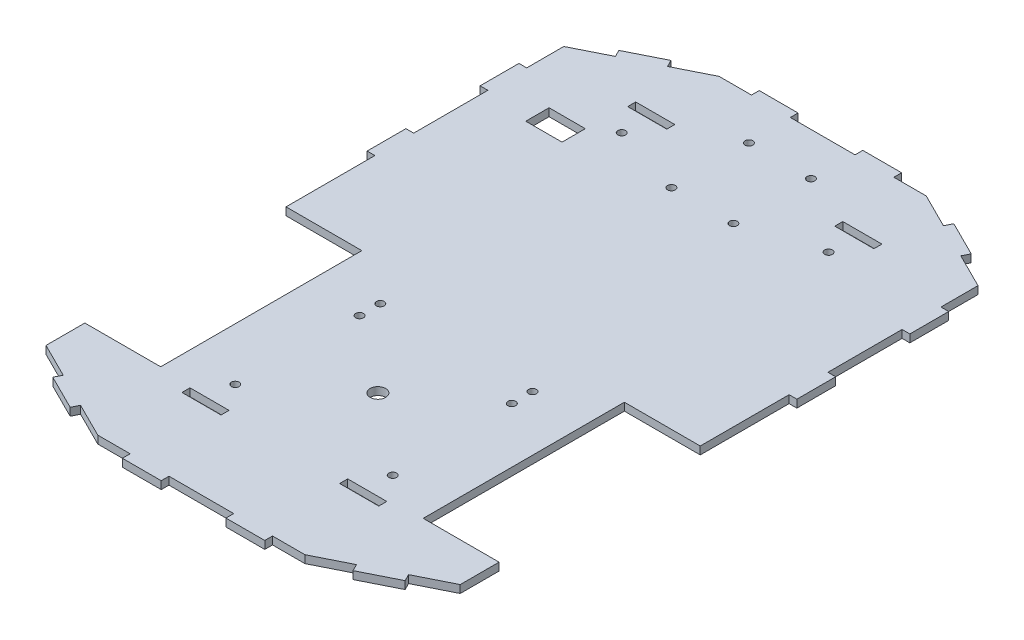
SolidWorks part; units mm, degrees
ref_plane "Front Plane" through (0, 0, 0) normal (0, 0, 1) x (1, 0, 0)
ref_plane "Top Plane" through (0, 0, 0) normal (0, 1, 0) x (1, 0, 0)
ref_plane "Right Plane" through (0, 0, 0) normal (1, 0, 0) x (0, 0, -1)
sketch "Sketch1" plane through (0, 0, 0) normal (0, 1, 0) x (1, 0, 0)
  line L0 (120, 0) -> (133.2918, 6.6459)
  line L1 (40, 0) -> (52.5, 0)
  line L2 (0, 20) -> (0, 35)
  line L3 (40, 240) -> (52.5, 240)
  line L4 (160, 20) -> (160, 35)
  line L5 (120, 240) -> (133.2918, 233.3541)
  line L6 (0, 20) -> (13.2918, 13.3541)
  line L7 (0, 220) -> (13.2918, 226.6459)
  line L8 (0, 35) -> (29.3, 35)
  line L9 (29.3, 35) -> (29.3, 112.71)
  line L10 (29.3, 112.71) -> (0, 112.71)
  line L11 (80, 240) -> (80, 0) construction
  line L12 (0, 112.71) -> (0, 147.0325)
  line L13 (160, 35) -> (130.7, 35)
  line L14 (130.7, 35) -> (130.7, 112.71)
  line L15 (130.7, 112.71) -> (160, 112.71)
  line L16 (160, 112.71) -> (160, 147.0325)
  line L17 (80, 213.7859) -> (0, 213.7859) construction
  line L18 (116.8791, 0) -> (116.8791, 25) construction
  line L19 (32.45, 212.2359) -> (47.55, 212.2359)
  line L20 (32.45, 212.2359) -> (32.45, 215.3359)
  line L21 (32.45, 215.3359) -> (47.55, 215.3359)
  line L22 (47.55, 212.2359) -> (47.55, 215.3359)
  line L23 (32.45, 212.2359) -> (47.55, 215.3359) construction
  line L24 (32.45, 215.3359) -> (47.55, 212.2359) construction
  line L25 (116.8791, 25) -> (97.8791, 25) construction
  line L26 (97.8791, 25) -> (97.8791, 0) construction
  line L27 (160, 32.0731) -> (0, 32.0731) construction
  line L28 (20, 230) -> (14.7857, 240.4286) construction
  line L29 (41.9927, 30.5231) -> (57.0927, 30.5231)
  line L30 (41.9927, 30.5231) -> (41.9927, 33.6231)
  line L31 (41.9927, 33.6231) -> (57.0927, 33.6231)
  line L32 (57.0927, 30.5231) -> (57.0927, 33.6231)
  line L33 (41.9927, 30.5231) -> (57.0927, 33.6231) construction
  line L34 (41.9927, 33.6231) -> (57.0927, 30.5231) construction
  line L35 (11.9502, 229.3292) -> (25.3666, 236.0374)
  line L36 (11.9502, 229.3292) -> (13.2918, 226.6459)
  line L37 (25.3666, 236.0374) -> (26.7082, 233.3541)
  line L38 (20, 10) -> (15, 0) construction
  line L39 (11.9502, 10.6708) -> (25.3666, 3.9626)
  line L40 (11.9502, 10.6708) -> (13.2918, 13.3541)
  line L41 (25.3666, 3.9626) -> (26.7082, 6.6459)
  line L42 (0, 176.355) -> (0, 190.6775) construction
  line L43 (0, 176.355) -> (0, 162.0325) construction
  line L44 (-3, 205.6775) -> (0, 205.6775)
  line L45 (-3, 205.6775) -> (-3, 190.6775)
  line L46 (-3, 190.6775) -> (0, 190.6775)
  line L48 (-3, 205.6775) -> (0, 198.1775) construction
  line L49 (-3, 190.6775) -> (0, 198.1775) construction
  line L51 (-3, 147.0325) -> (0, 147.0325)
  line L52 (-3, 147.0325) -> (-3, 162.0325)
  line L53 (-3, 162.0325) -> (0, 162.0325)
  line L55 (-3, 147.0325) -> (0, 154.5325) construction
  line L56 (-3, 162.0325) -> (0, 154.5325) construction
  line L57 (0, 205.6775) -> (0, 220)
  line L58 (0, 205.6775) -> (0, 220) construction
  line L59 (0, 162.0325) -> (0, 190.6775)
  line L60 (0, 147.0325) -> (0, 112.71) construction
  line L61 (26.7082, 233.3541) -> (40, 240)
  line L62 (26.7082, 6.6459) -> (40, 0)
  line L63 (40, 240) -> (52.5, 240) construction
  line L64 (40, 0) -> (52.5, 0) construction
  line L66 (52.5, 240) -> (52.5, 243)
  line L67 (52.5, 243) -> (67.5, 243)
  line L68 (67.5, 240) -> (67.5, 243)
  line L69 (60, 240) -> (67.5, 243) construction
  line L70 (52.5, 243) -> (60, 240) construction
  line L71 (67.5, 0) -> (80, 0) construction
  line L72 (52.5, -3) -> (67.5, -3)
  line L73 (52.5, -3) -> (52.5, 0)
  line L75 (67.5, -3) -> (67.5, 0)
  line L76 (67.5, 240) -> (92.5, 240)
  line L77 (67.5, 240) -> (80, 240) construction
  line L78 (67.5, 0) -> (92.5, 0)
  line L79 (112.45, 212.2359) -> (112.45, 215.3359)
  line L80 (127.55, 212.2359) -> (127.55, 215.3359)
  line L81 (127.55, 212.2359) -> (112.45, 212.2359)
  line L82 (127.55, 215.3359) -> (112.45, 215.3359)
  line L83 (92.5, 240) -> (92.5, 243)
  line L84 (107.5, 243) -> (92.5, 243)
  line L85 (107.5, 240) -> (107.5, 243)
  line L86 (134.6334, 236.0374) -> (133.2918, 233.3541)
  line L87 (148.0498, 229.3292) -> (134.6334, 236.0374)
  line L88 (148.0498, 229.3292) -> (146.7082, 226.6459)
  line L89 (163, 205.6775) -> (160, 205.6775)
  line L90 (163, 205.6775) -> (163, 190.6775)
  line L91 (163, 190.6775) -> (160, 190.6775)
  line L92 (163, 162.0325) -> (160, 162.0325)
  line L93 (163, 147.0325) -> (163, 162.0325)
  line L94 (163, 147.0325) -> (160, 147.0325)
  line L95 (148.0498, 10.6708) -> (146.7082, 13.3541)
  line L96 (148.0498, 10.6708) -> (134.6334, 3.9626)
  line L97 (134.6334, 3.9626) -> (133.2918, 6.6459)
  line L98 (107.5, -3) -> (107.5, 0)
  line L99 (92.5, -3) -> (92.5, 0)
  line L100 (107.5, -3) -> (92.5, -3)
  line L101 (118.0073, 33.6231) -> (102.9073, 30.5231) construction
  line L102 (118.0073, 30.5231) -> (102.9073, 33.6231) construction
  line L103 (102.9073, 30.5231) -> (102.9073, 33.6231)
  line L104 (118.0073, 33.6231) -> (102.9073, 33.6231)
  line L105 (118.0073, 30.5231) -> (118.0073, 33.6231)
  line L106 (118.0073, 30.5231) -> (102.9073, 30.5231)
  line L107 (107.5, 0) -> (120, 0)
  line L108 (146.7082, 13.3541) -> (160, 20)
  line L109 (160, 162.0325) -> (160, 190.6775)
  line L110 (160, 205.6775) -> (160, 220)
  line L111 (146.7082, 226.6459) -> (160, 220)
  line L112 (107.5, 240) -> (120, 240)
  line L114 (17.6584, 196.6591) -> (31.6584, 196.6591)
  line L115 (17.6584, 196.6591) -> (17.6584, 187.6591)
  line L116 (17.6584, 187.6591) -> (31.6584, 187.6591)
  line L117 (31.6584, 196.6591) -> (31.6584, 187.6591)
  circle A0 centre (50.6, 98.52) radius 1.5
  circle A1 centre (50.6, 90.52) radius 1.5
  circle A2 centre (68.025, 223.5) radius 1.5
  circle A3 centre (68.025, 193.55) radius 1.5
  circle A6 centre (91.975, 193.55) radius 1.5
  circle A7 centre (91.975, 223.5) radius 1.5
  circle A8 centre (109.4, 90.52) radius 1.5
  circle A9 centre (109.4, 98.52) radius 1.5
  circle A10 centre (40.05, 202.3359) radius 1.5
  circle A11 centre (49.5927, 43.5152) radius 1.5
  circle A13 centre (110.4073, 43.5152) radius 1.5
  circle A14 centre (119.95, 202.3359) radius 1.5
  circle A15 centre (80, 68.1979) radius 3
  point P0 (0, 0)
  point P1 (160, 240)
  point P2 (0, 240)
  point P3 (160, 0)
  point P25 (40, 213.7859)
  point P52 (49.5427, 32.0731)
  point P62 (18.6584, 232.6833)
  point P66 (0, 198.1775)
  point P69 (18.6584, 7.3167)
  point P77 (0, 154.5325)
  point P81 (60, 240)
  point P88 (60, 0)
  point P127 (110.4573, 32.0731)
  dimension "D14" = 3
  dimension "D19" = 3
  dimension "D20" = 16.5
  dimension "D42" = 3
  dimension "D43" = 3
  dimension "D45" = 6
  dimension "D1" = 160
  dimension "D2" = 240
  dimension "D3" = 40
  dimension "D4" = 20
  dimension "D5" = 40
  dimension "D6" = 20
  dimension "D7" = 40
  dimension "D8" = 20
  dimension "D9" = 20
  dimension "D10" = 40
  dimension "D11" = 29.3
  dimension "D12" = 77.71
  dimension "D13" = 15
  dimension "D15" = 63.52
  dimension "D16" = 50.6
  dimension "D17" = 8
  dimension "D18" = 50.6
  dimension "D21" = 11.975
  dimension "D22" = 29.95
  dimension "D23" = 11.975
  dimension "D24" = 3.1
  dimension "D25" = 15.1
  dimension "D26" = 25
  dimension "D27" = 19
  dimension "D28" = 3.1
  dimension "D29" = 15.1
  dimension "D30" = 15
  dimension "D31" = 3
  dimension "D32" = 15
  dimension "D33" = 3
  dimension "D34" = 15
  dimension "D35" = 15
  dimension "D36" = 3
  dimension "D37" = 3
  dimension "D38" = 15
  dimension "D39" = 3
  dimension "D40" = 15
  dimension "D41" = 3
  dimension "D44" = 9.9
  dimension "D46" = 14
  dimension "D47" = 9
extrude "Boss-Extrude1" add sketch "Sketch1" along normal blind 3
